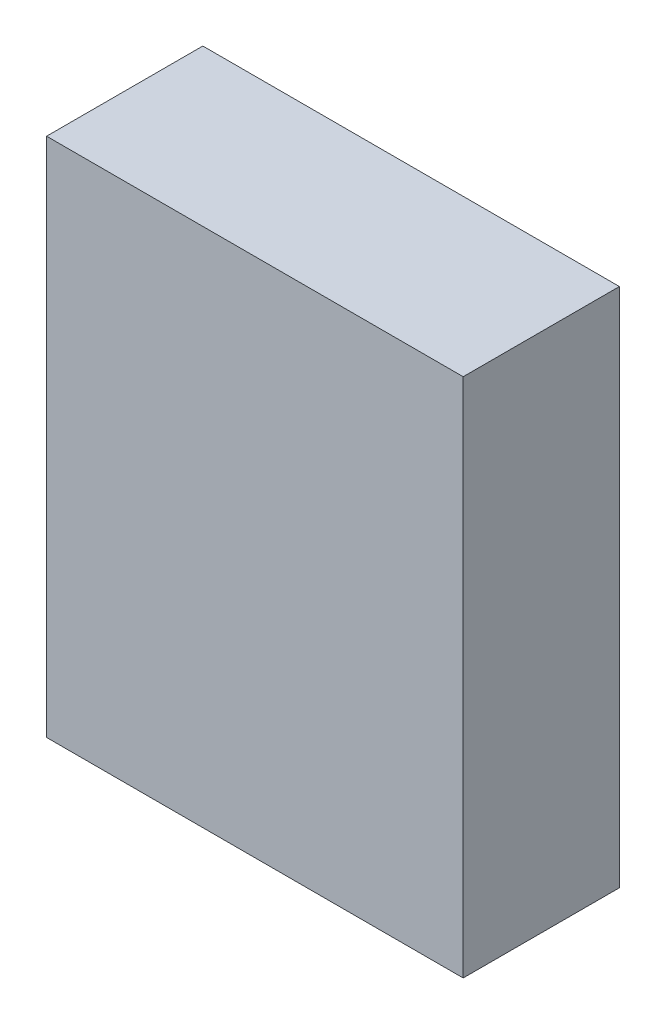
SolidWorks part; units mm, degrees
material "Silicon Dioxide"
ref_plane "Front Plane" through (0, 0, 0) normal (0, 0, 1) x (1, 0, 0)
ref_plane "Top Plane" through (0, 0, 0) normal (0, 1, 0) x (1, 0, 0)
ref_plane "Right Plane" through (0, 0, 0) normal (1, 0, 0) x (0, 0, -1)
sketch "Sketch1" plane through (0, 0, 0) normal (0, 0, 1) x (1, 0, 0)
  line L1 (-75.6362, 48.0134) -> (4.3638, 48.0134)
  line L2 (-75.6362, 48.0134) -> (-75.6362, -51.9866)
  line L3 (-75.6362, -51.9866) -> (4.3638, -51.9866)
  line L4 (4.3638, 48.0134) -> (4.3638, -51.9866)
  dimension "D1" = 80
  dimension "D2" = 100
extrude "Boss-Extrude1" add sketch "Sketch1" along normal blind 30
